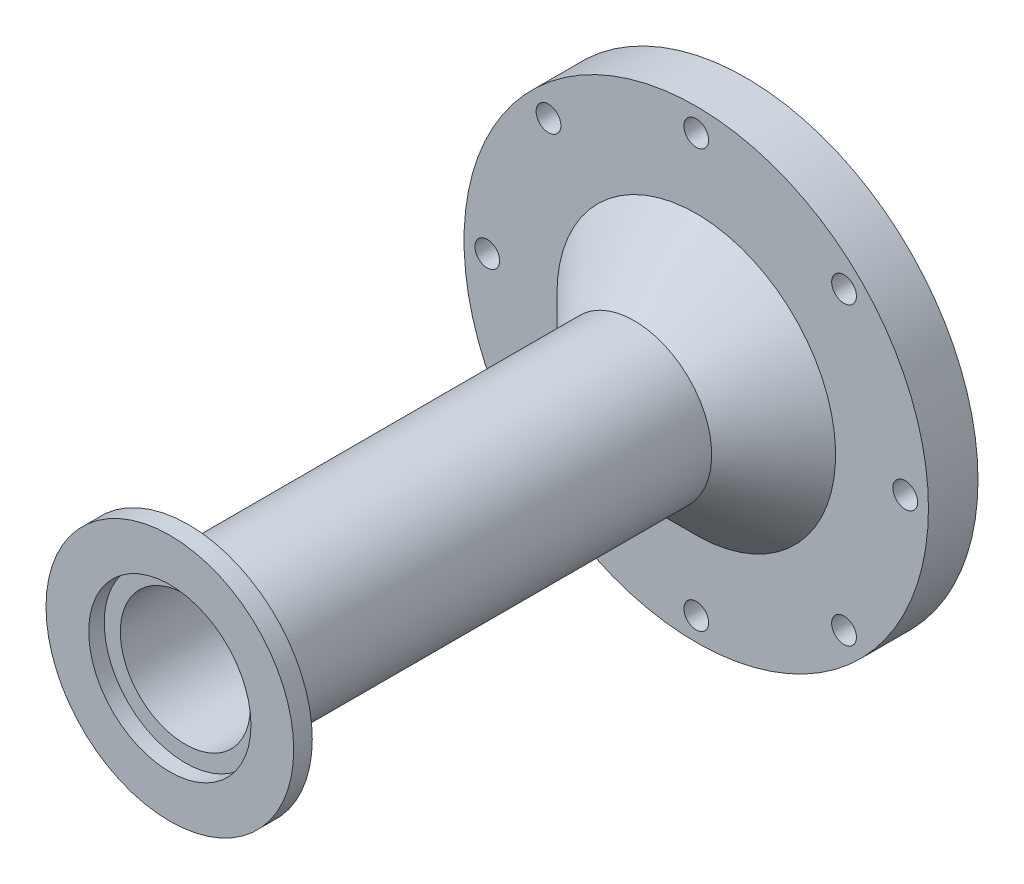
SolidWorks part; units mm, degrees
material "AISI 316 Stainless Steel Sheet (SS)"
ref_plane "Front Plane" through (0, 0, 0) normal (0, 0, 1) x (1, 0, 0)
ref_plane "Top Plane" through (0, 0, 0) normal (0, 1, 0) x (1, 0, 0)
ref_plane "Right Plane" through (0, 0, 0) normal (1, 0, 0) x (0, 0, -1)
sketch "Sketch1" plane through (0, 0, 0) normal (0, 0, 1) x (1, 0, 0)
  circle A0 centre (0, 0) radius 20.71 construction
  circle A1 centre (0, 0) radius 20.71
  circle A2 centre (0, 0) radius 19.21 construction
  circle A3 centre (0, 0) radius 19.21
  circle A5 centre (0, 0) radius 37.5 construction
  circle A6 centre (23.8649, -23.8649) radius 2 construction
  circle A7 centre (33.75, 0) radius 2 construction
  circle A8 centre (-23.8649, 23.8649) radius 2 construction
  circle A9 centre (-33.75, 0) radius 2 construction
  circle A10 centre (-23.8649, -23.8649) radius 2 construction
  circle A11 centre (0, -33.75) radius 2 construction
  circle A12 centre (23.8649, -23.8649) radius 2
  circle A13 centre (33.75, 0) radius 2
  circle A14 centre (-23.8649, 23.8649) radius 2
  circle A15 centre (-33.75, 0) radius 2
  circle A16 centre (-23.8649, -23.8649) radius 2
  circle A17 centre (0, -33.75) radius 2
  circle A18 centre (0, 0) radius 37.5
sketch "Sketch2" plane through (0, 0, 0) normal (0, 0, 1) x (1, 0, 0)
  circle A1 centre (0, 0) radius 37.5 construction
  circle A2 centre (0, 0) radius 5.35 construction
  circle A3 centre (0, 0) radius 5.35
  circle A4 centre (0, 0) radius 37.5
extrude "Boss-Extrude2" add sketch "Sketch2" along normal blind 8
sketch "Sketch3" plane through (0, 0, 0) normal (0, 0, 1) x (1, 0, 0)
  circle A0 centre (0, 0) radius 20.71 construction
  circle A1 centre (0, 0) radius 20.71
  circle A2 centre (0, 0) radius 19.21 construction
  circle A3 centre (0, 0) radius 19.21
sketch "Sketch14" plane through (0, 0, 0) normal (0, 0, 1) x (1, 0, 0)
  circle A7 centre (0, 33.75) radius 2
  circle A8 centre (0, 33.75) radius 2
  circle A9 centre (-23.8649, 23.8649) radius 2
  circle A10 centre (-23.8649, 23.8649) radius 2
  circle A11 centre (-33.75, 0) radius 2
  circle A12 centre (-33.75, 0) radius 2
  circle A13 centre (-23.8649, -23.8649) radius 2
  circle A14 centre (-23.8649, -23.8649) radius 2
  circle A15 centre (0, -33.75) radius 2
  circle A16 centre (0, -33.75) radius 2
  circle A17 centre (23.8649, -23.8649) radius 2
  circle A18 centre (23.8649, -23.8649) radius 2
  circle A19 centre (33.75, 0) radius 2
  circle A20 centre (33.75, 0) radius 2
  circle A21 centre (23.8649, 23.8649) radius 2
  circle A22 centre (23.8649, 23.8649) radius 2
  dimension "D1" = 0
  dimension "D2" = 0
  dimension "D3" = 0
  dimension "D4" = 0
  dimension "D5" = 0
  dimension "D6" = 0
  dimension "D7" = 0
  dimension "D8" = 0
extrude "Cut-Extrude6" cut sketch "Sketch14" along normal through all
extrude "Cut-Extrude2" cut sketch "Sketch3" along normal blind 2
sketch "Sketch6" plane through (0, 0, 8) normal (0, 0, 1) x (1, 0, 0)
  circle A1 centre (0, 0) radius 10.45
  circle A2 centre (0, 0) radius 5.35 construction
  circle A3 centre (0, 0) radius 6.45
  dimension "D1" = 1.1
  dimension "D2" = 4
extrude "Boss-Extrude3" [suppressed] add sketch "Sketch6" along normal blind 40
sketch "Sketch7" plane through (0, 0, 8) normal (0, 0, 1) x (1, 0, 0)
  circle A0 centre (0, 0) radius 12.5
  circle A1 centre (0, 0) radius 10.5
  dimension "D1" = 25
  dimension "D2" = 2
extrude "Boss-Extrude4" add sketch "Sketch7" along normal blind 80
sketch "Sketch10" plane through (0, 0, 88) normal (0, 0, 1) x (1, 0, 0)
  circle A0 centre (0, 0) radius 12.5 construction
  circle A1 centre (0, 0) radius 12.5
extrude "Boss-Extrude5" add sketch "Sketch10" along normal blind 2.01 draft 75 draft outward yes
sketch "Sketch11" plane through (0, 0, 90.01) normal (0, 0, 1) x (1, 0, 0)
  circle A1 centre (0, 0) radius 10.5 construction
  circle A2 centre (0, 0) radius 10.5
extrude "Cut-Extrude3" cut sketch "Sketch11" against normal through all
sketch "Sketch12" plane through (0, 0, 90.01) normal (0, 0, 1) x (1, 0, 0)
  circle A0 centre (0, 0) radius 10.5 construction
  circle A1 centre (0, 0) radius 20.0014 construction
  circle A2 centre (0, 0) radius 10.5
  circle A3 centre (0, 0) radius 20.0014
extrude "Boss-Extrude6" add sketch "Sketch12" along normal blind 3
sketch "Sketch13" plane through (0, 0, 93.01) normal (0, 0, 1) x (1, 0, 0)
  circle A0 centre (0, 0) radius 13.1
  dimension "D1" = 26.2
extrude "Cut-Extrude4" cut sketch "Sketch13" against normal blind 2.5
chamfer "Chamfer1" distance 10 angle 45 1 edges at (12.5, 0, 8)
chamfer "Chamfer2" [suppressed] distance 10 angle 45
sketch "Sketch15" [suppressed] plane through (0, 0, 48) normal (0, 0, 1) x (1, 0, 0)
  circle A2 centre (0, 0) radius 7.35
  circle A3 centre (0, 0) radius 7.35
  dimension "D1" = 2
extrude "Cut-Extrude7" [suppressed] cut sketch "Sketch15" against normal blind 10
